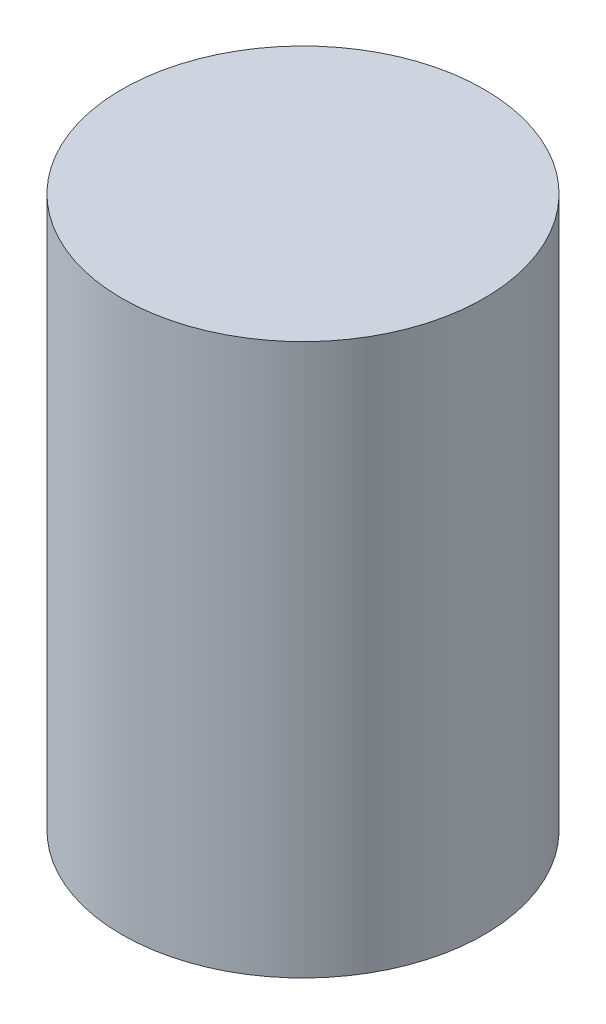
SolidWorks part; units mm, degrees
ref_plane "Front Plane" through (0, 0, 0) normal (0, 0, 1) x (1, 0, 0)
ref_plane "Top Plane" through (0, 0, 0) normal (0, 1, 0) x (1, 0, 0)
ref_plane "Right Plane" through (0, 0, 0) normal (1, 0, 0) x (0, 0, -1)
sketch "Sketch1" plane through (0, 0, 0) normal (0, 1, 0) x (1, 0, 0)
  circle A0 centre (0, 0) radius 292.1
  dimension "D1" = 584.2
extrude "Boss-Extrude1" add sketch "Sketch1" along normal blind 889
